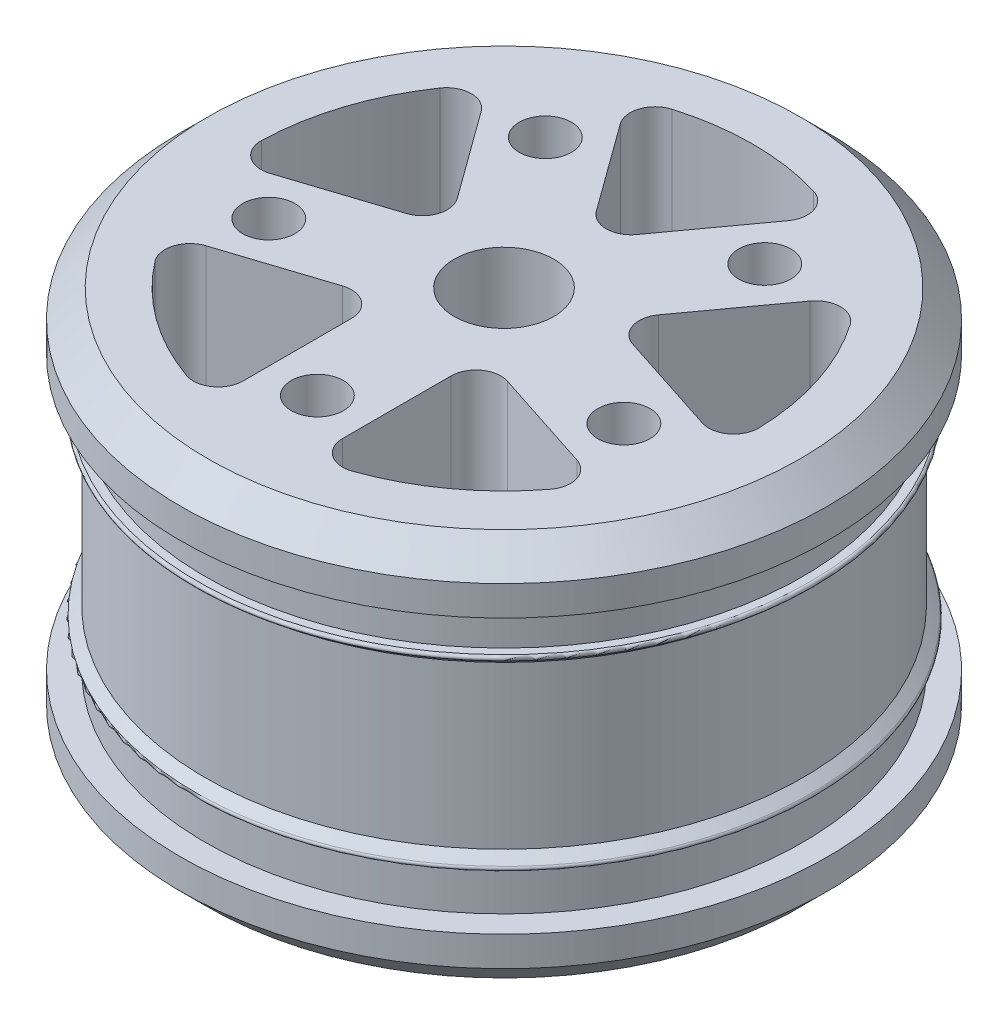
SolidWorks part; units mm, degrees
ref_plane "前视基准面" through (0, 0, 0) normal (0, 0, 1) x (1, 0, 0)
ref_plane "上视基准面" through (0, 0, 0) normal (0, 1, 0) x (1, 0, 0)
ref_plane "右视基准面" through (0, 0, 0) normal (1, 0, 0) x (0, 0, -1)
sketch "草图2" plane through (0, 0, 0) normal (0, 0, 1) x (1, 0, 0)
  line L0 (0, 24.0341) -> (0, -24.0341) construction
  line L1 (0, 15.6) -> (0, -15.6)
  line L2 (0, -15.6) -> (26, -15.6)
  line L3 (26, -15.6) -> (26, -11)
  line L4 (26, -11) -> (24, -11)
  line L5 (24, -11) -> (24, -7.5)
  line L6 (24, 11) -> (26, 11)
  line L7 (26, 11) -> (26, 15.6)
  line L8 (26, 15.6) -> (0, 15.6)
  line L9 (24, 0) -> (0, 0) construction
  line L10 (24, 7.5) -> (25.2, 7.5)
  line L11 (25.2, 7.5) -> (24, 6.5)
  line L12 (24, -7.5) -> (25.2, -7.5)
  line L13 (25.2, -7.5) -> (24, -6.5)
  line L14 (25.2, 7.5) -> (25.2, -7.5) construction
  line L15 (24, 7.5) -> (24, 11)
  line L16 (24, -6.5) -> (24, 6.5)
  point P3 (0, 0)
  point P6 (0, 0)
  point P20 (25.2, 0)
  point P24 (24, 0)
  dimension "D1" = 26
  dimension "D2" = 31.2
  dimension "D3" = 22
  dimension "D4" = 2
  dimension "D5" = 15
  dimension "D6" = 13
  dimension "D7" = 1.2
revolve "旋转1" add sketch "草图2" angle 360 about L0
fillet "圆角1" radius 0.2 2 edges at (-25.2, 7.5, 0) (-25.2, -7.5, 0)
sketch "草图6" plane through (0, -15.6, 0) normal (0, -1, 0) x (1, 0, 0)
  line L0 (0, 0) -> (19.0211, -6.1803) construction
  line L14 (9.0902, -1.2523) -> (17.376, 1.44)
  line L15 (8.0902, -4.33) -> (13.2111, -11.3783)
  arc A0 (16.4768, -11.3364) -> (19.9934, -0.5135) centre (0, 0) ccw
  arc A5 (9.0902, -1.2523) -> (8.0902, -4.33) centre (9.7082, -3.1544) ccw
  arc A6 (19.9934, -0.5135) -> (17.376, 1.44) centre (17.9941, -0.4621) ccw
  arc A7 (16.4768, -11.3364) -> (13.2111, -11.3783) centre (14.8291, -10.2028) cw
  dimension "D1" = 20
  dimension "D2" = 2
  dimension "D3" = 36
  dimension "D4" = 36
extrude "切除-拉伸2" cut sketch "草图6" against normal up to next
pattern_circular "阵列(圆周)1" count 5 over 360 about axis through (0, 0, 0) along (0, 1, 0) of "切除-拉伸2"
sketch "草图8" plane through (0, 15.6, 0) normal (0, 1, 0) x (1, 0, 0)
  circle A0 centre (0, 0) radius 4
  dimension "D1" = 8
extrude "切除-拉伸3" cut sketch "草图8" against normal up to next
sketch "草图9" plane through (0, 15.6, 0) normal (0, 1, 0) x (1, 0, 0)
  circle A0 centre (0, -15) radius 2.1
  dimension "D2" = 4.2
  dimension "D1" = 15
extrude "切除-拉伸4" cut sketch "草图9" against normal up to next
pattern_circular "阵列(圆周)2" count 5 every 72 about axis through (0, 0, 0) along (0, 1, 0) of "切除-拉伸4"
chamfer "倒角1" distance 2.2 angle 45 2 edges at (-26, -15.6, 0) (-26, 15.6, 0)
